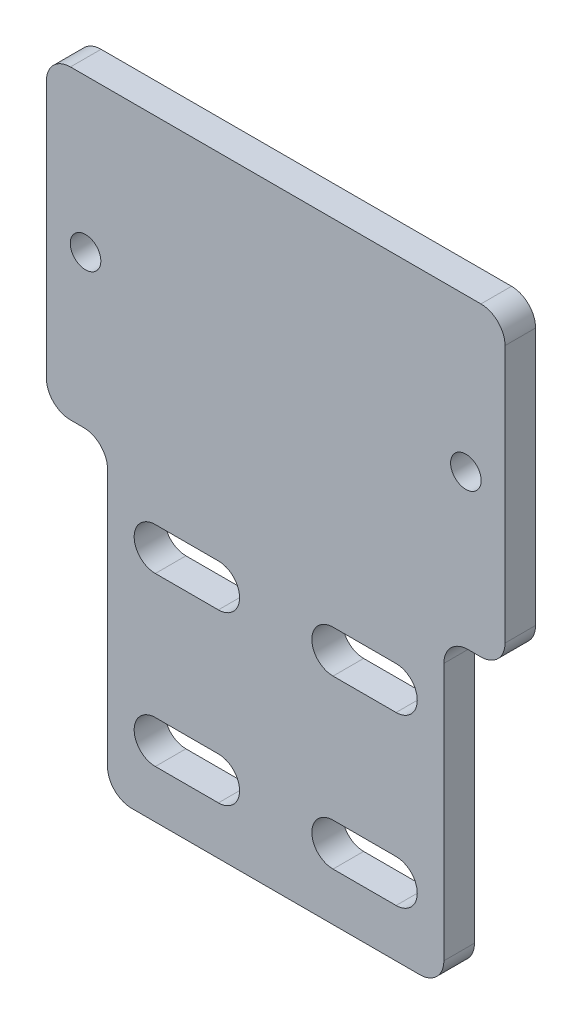
SolidWorks part; units mm, degrees
ref_plane "Front Plane" through (0, 0, 0) normal (0, 0, 1) x (1, 0, 0)
ref_plane "Top Plane" through (0, 0, 0) normal (0, 1, 0) x (1, 0, 0)
ref_plane "Right Plane" through (0, 0, 0) normal (1, 0, 0) x (0, 0, -1)
sketch "Sketch1" plane through (0, 0, 0) normal (0, 0, 1) x (1, 0, 0)
  line L0 (0, 0) -> (0, 63.5)
  line L1 (0, 63.5) -> (-12.7, 63.5)
  line L2 (-12.7, 63.5) -> (-12.7, 127)
  line L3 (-12.7, 127) -> (82.55, 127)
  line L4 (82.55, 127) -> (82.55, 63.5)
  line L5 (82.55, 63.5) -> (69.85, 63.5)
  line L6 (69.85, 63.5) -> (69.85, 0)
  line L7 (69.85, 0) -> (0, 0)
  line L8 (34.925, 127) -> (34.925, 0) construction
  point P11 (0, 0)
  dimension "D1" = 95.25
  dimension "D2" = 69.85
  dimension "D3" = 63.5
  dimension "D4" = 63.5
extrude "Boss-Extrude1" add sketch "Sketch1" along normal blind 6.35
sketch "Sketch2" plane through (0, 0, 6.35) normal (0, 0, 1) x (1, 0, 0)
  line L0 (-12.7, 95.25) -> (82.55, 95.25) construction
  line L1 (-12.7, 127) -> (-12.7, 63.5) construction
  line L2 (82.55, 63.5) -> (82.55, 127) construction
  line L3 (34.925, 127) -> (34.925, 0) construction
  line L4 (82.55, 127) -> (-12.7, 127) construction
  line L5 (0, 0) -> (69.85, 0) construction
  circle A0 centre (-4.572, 95.25) radius 3.175
  circle A1 centre (74.422, 95.25) radius 3.175
  point P14 (0, 0)
  dimension "D2" = 6.35
  dimension "D1" = 39.497
extrude "Cut-Extrude1" cut sketch "Sketch2" against normal up to next
sketch "Sketch3" plane through (0, 0, 6.35) normal (0, 0, 1) x (1, 0, 0)
  line L0 (9.925, 49.1054) -> (23.0187, 49.1054) construction
  line L1 (9.925, 53.5054) -> (23.0187, 53.5054)
  line L2 (9.925, 44.7054) -> (23.0187, 44.7054)
  line L3 (34.925, 127) -> (34.925, 0) construction
  line L4 (82.55, 127) -> (-12.7, 127) construction
  line L5 (0, 0) -> (69.85, 0) construction
  line L6 (59.925, 49.1054) -> (46.8312, 49.1054) construction
  line L7 (59.925, 53.5054) -> (46.8312, 53.5054)
  line L8 (59.925, 44.7054) -> (46.8312, 44.7054)
  line L9 (0, 31.75) -> (69.85, 31.75) construction
  line L10 (0, 63.5) -> (0, 0) construction
  line L11 (69.85, 0) -> (69.85, 63.5) construction
  line L12 (59.925, 14.3946) -> (46.8312, 14.3946) construction
  line L13 (59.925, 9.9946) -> (46.8312, 9.9946)
  line L14 (59.925, 18.7946) -> (46.8312, 18.7946)
  line L15 (9.925, 14.3946) -> (23.0187, 14.3946) construction
  line L16 (9.925, 9.9946) -> (23.0187, 9.9946)
  line L17 (9.925, 18.7946) -> (23.0187, 18.7946)
  arc A0 (9.925, 53.5054) -> (9.925, 44.7054) centre (9.925, 49.1054) ccw
  arc A1 (23.0187, 44.7054) -> (23.0187, 53.5054) centre (23.0187, 49.1054) ccw
  arc A2 (59.925, 53.5054) -> (59.925, 44.7054) centre (59.925, 49.1054) cw
  arc A3 (46.8312, 44.7054) -> (46.8312, 53.5054) centre (46.8312, 49.1054) cw
  arc A4 (59.925, 9.9946) -> (59.925, 18.7946) centre (59.925, 14.3946) ccw
  arc A5 (46.8312, 18.7946) -> (46.8312, 9.9946) centre (46.8312, 14.3946) ccw
  arc A6 (9.925, 9.9946) -> (9.925, 18.7946) centre (9.925, 14.3946) cw
  arc A7 (23.0187, 18.7946) -> (23.0187, 9.9946) centre (23.0187, 14.3946) cw
  point P2 (16.4719, 49.1054)
  point P15 (53.3781, 49.1054)
  point P28 (53.3781, 14.3946)
  point P35 (16.4719, 14.3946)
  dimension "D3" = 4.4
  dimension "D1" = 11.9062
  dimension "D2" = 25
extrude "Cut-Extrude2" cut sketch "Sketch3" against normal up to next
fillet "Fillet1" radius 5 8 edges at (-12.7, 127, 3.175) (82.55, 127, 3.175) (82.55, 63.5, 3.175) (69.85, 63.5, 3.175) (69.85, 0, 3.175) (0, 0, 3.175) (-12.7, 63.5, 3.175) (0, 63.5, 3.175)
